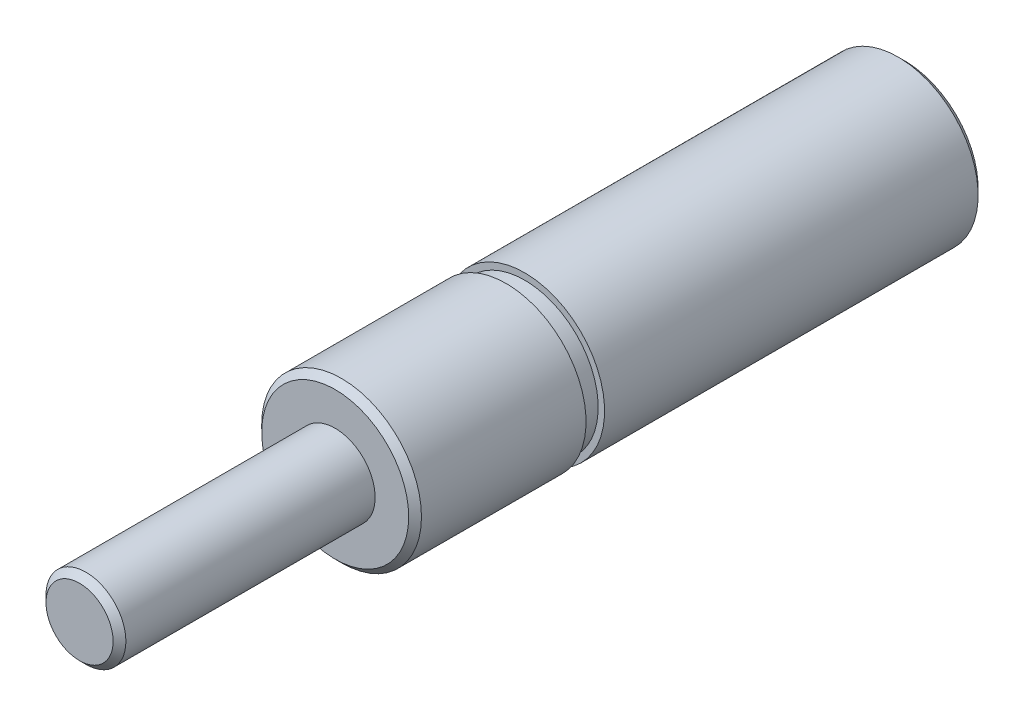
SolidWorks part; units mm, degrees
material "6061-T6 (SS)"
ref_plane "Front Plane" through (0, 0, 0) normal (0, 0, 1) x (1, 0, 0)
ref_plane "Top Plane" through (0, 0, 0) normal (0, 1, 0) x (1, 0, 0)
ref_plane "Right Plane" through (0, 0, 0) normal (1, 0, 0) x (0, 0, -1)
sketch "Sketch1" plane through (0, 0, 0) normal (1, 0, 0) x (0, 0, -1)
  line L0 (0, 0) -> (0, 1.5875)
  line L1 (0, 1.5875) -> (10.16, 1.5875)
  line L2 (10.16, 1.5875) -> (10.16, 3.175)
  line L3 (10.16, 3.175) -> (16.9545, 3.175)
  line L4 (32.7914, 3.175) -> (32.7914, 1.5875)
  line L5 (26.4414, 0) -> (0, 0)
  line L6 (17.6911, 3.175) -> (17.6911, 2.921)
  line L7 (16.9545, 3.175) -> (16.9545, 2.921)
  line L8 (16.9545, 2.921) -> (17.6911, 2.921)
  line L9 (17.6911, 3.175) -> (32.7914, 3.175)
  line L10 (32.7914, 1.5875) -> (26.4414, 1.5875)
  line L11 (26.4414, 1.5875) -> (26.4414, 0)
  line L12 (-6.5321, 0) -> (56.6202, 0) construction
  dimension "D1" = 3.175
  dimension "D2" = 10.16
  dimension "D3" = 6.35
  dimension "D4" = 22.6314
  dimension "D5" = 0.7366
  dimension "D6" = 2.921
  dimension "D7" = 15.8369
  dimension "D8" = 3.175
  dimension "D9" = 6.35
revolve "Revolve1" add sketch "Sketch1" angle 360 about L5
chamfer "Chamfer1" distance 0.254 angle 45 3 edges at (-1.5875, 0, 0) (-3.175, 0, -10.16) (-3.175, 0, -32.7914)
